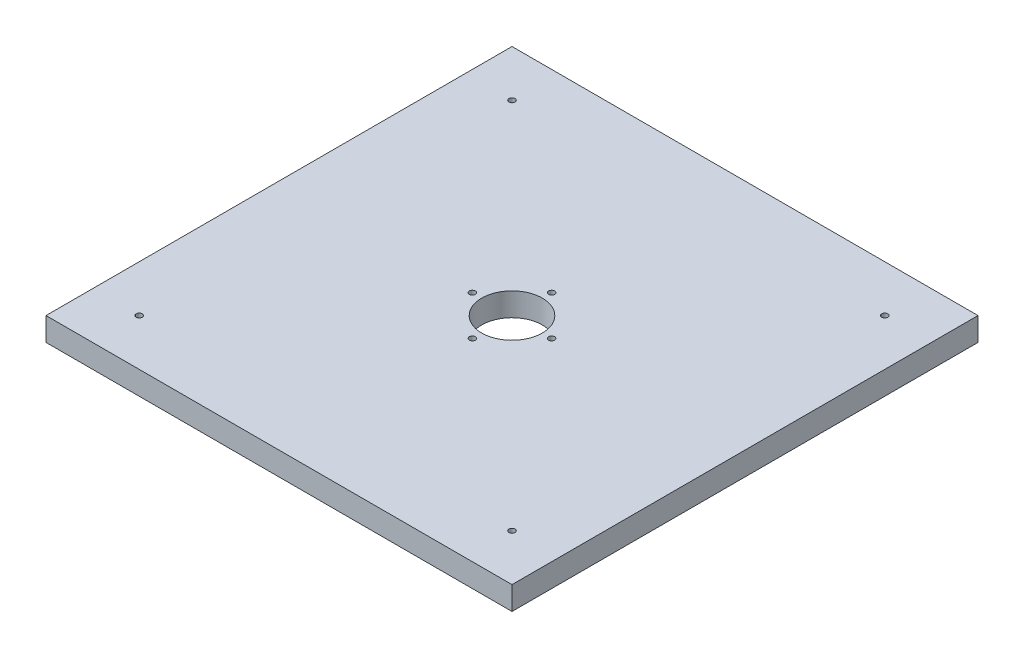
SolidWorks part; units mm, degrees
ref_plane "Front Plane" through (0, 0, 0) normal (0, 0, 1) x (1, 0, 0)
ref_plane "Top Plane" through (0, 0, 0) normal (0, 1, 0) x (1, 0, 0)
ref_plane "Right Plane" through (0, 0, 0) normal (1, 0, 0) x (0, 0, -1)
sketch "Sketch1" plane through (0, 0, 0) normal (0, 1, 0) x (1, 0, 0)
  line L1 (0, 0) -> (200, 0)
  line L2 (0, 0) -> (0, 200)
  line L3 (0, 200) -> (200, 200)
  line L4 (200, 0) -> (200, 200)
  line L5 (0, 0) -> (200, 200) construction
  line L6 (0, 200) -> (200, 0) construction
  point P4 (67.5676, 55.1874)
  dimension "D1" = 200
  dimension "D2" = 200
extrude "Boss-Extrude1" add sketch "Sketch1" along normal blind 10
sketch "Sketch2" plane through (0, 0, 0) normal (0, 1, 0) x (1, 0, 0)
  circle A0 centre (100, 100) radius 13
extrude "Cut-Extrude2" cut sketch "Sketch2" against normal through all both and the other way through all
sketch "Sketch3" plane through (0, 10, 0) normal (0, 1, 0) x (1, 0, 0)
  point P0 (20, 180)
  point P2 (180, 180)
  point P4 (180, 20)
  point P6 (20, 20)
  point P8 (100, 117)
  point P10 (117, 100)
  point P12 (100, 83)
  point P14 (83, 100)
hole_wizard "Tap Drill for M3x0.5 Tap1" positions "Sketch3" profile "Sketch4" hole size "M3x0.5" standard "JIS" end condition through all
sketch "Sketch4" plane through (20, 10, -180) normal (1, 0, 0) x (0, 0, 1)
  line L0 (0, 0) -> (0, 10)
  line L1 (0, 10) -> (1.3, 10)
  line L2 (1.3, 10) -> (1.3, 0)
  line L5 (1.3, 0) -> (0, 0)
  line L11 (0, -6.35) -> (0, 107.95) construction
  dimension "Thru Hole Dia." = 2.6
  dimension "Thru Hole Depth" = 10
